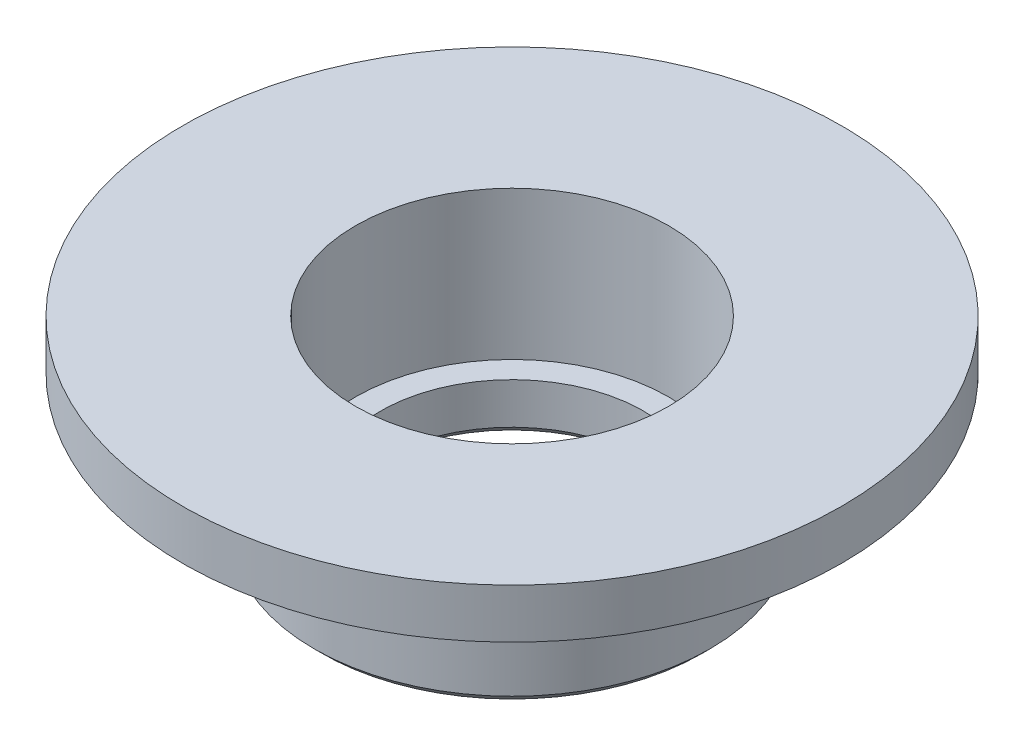
SolidWorks part; units mm, degrees
material "Lega 1060"
ref_plane "Piano frontale" through (0, 0, 0) normal (0, 0, 1) x (1, 0, 0)
ref_plane "Piano superiore" through (0, 0, 0) normal (0, 1, 0) x (1, 0, 0)
ref_plane "Piano destro" through (0, 0, 0) normal (1, 0, 0) x (0, 0, -1)
sketch "Schizzo1" plane through (0, 0, 0) normal (0, 0, 1) x (1, 0, 0)
  line L0 (0, -37.4526) -> (0, 37.4526) construction
  line L1 (9.5, 0) -> (20, 0)
  line L2 (20, 0) -> (20, -3)
  line L3 (20, -3) -> (12, -3)
  line L4 (12, -3) -> (12, -12)
  line L5 (12, -12) -> (8, -12)
  line L6 (8, -12) -> (8, -9)
  line L7 (8, -9) -> (9.5, -9)
  line L8 (9.5, -9) -> (9.5, 0)
  point P3 (0, 0)
  dimension "D1" = 9.5
  dimension "D2" = 8
  dimension "D3" = 12
  dimension "D4" = 3
  dimension "D5" = 12
  dimension "D6" = 3
  dimension "D7" = 20
revolve "Rivoluzione1" add sketch "Schizzo1" angle 360 about L0
chamfer "Smusso1" distance 0.5 angle 45 2 edges at (12, -12, 0) (8, -12, 0)
